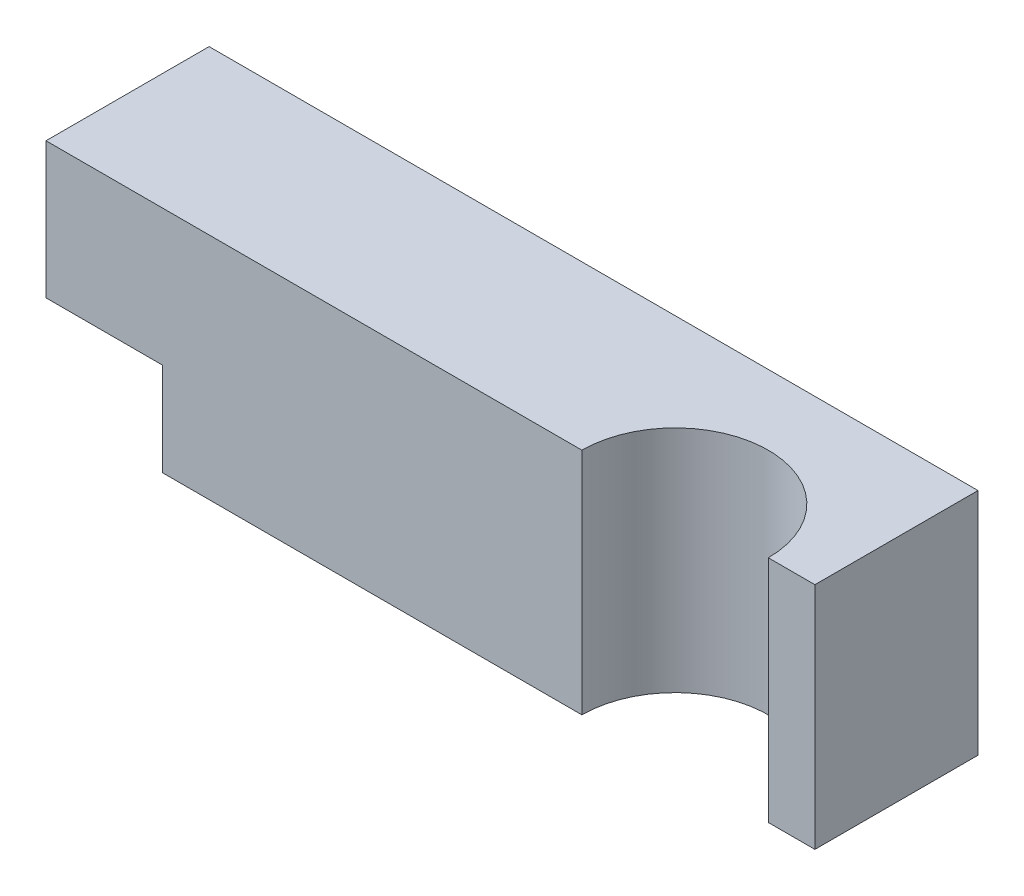
SolidWorks part; units mm, degrees
ref_plane "Front Plane" through (0, 0, 0) normal (0, 0, 1) x (1, 0, 0)
ref_plane "Top Plane" through (0, 0, 0) normal (0, 1, 0) x (1, 0, 0)
ref_plane "Right Plane" through (0, 0, 0) normal (1, 0, 0) x (0, 0, -1)
sketch "Sketch4" plane through (0, 0, 0) normal (0, 0, 1) x (1, 0, 0)
  line L1 (30.8815, 14.9647) -> (16.8815, 14.9647)
  line L2 (30.8815, 14.9647) -> (30.8815, 16.9647)
  line L4 (16.8815, 14.9647) -> (16.8815, 16.9647)
  line L5 (20.7026, 19.8847) -> (30.8815, 19.8847)
  line L6 (16.8815, 16.9647) -> (14.3815, 16.9647)
  line L8 (20.7026, 19.8847) -> (14.3815, 19.8847)
  line L9 (14.3815, 16.9647) -> (14.3815, 19.8847)
  line L10 (30.8815, 19.8847) -> (30.8815, 16.9647)
extrude "Boss-Extrude2" add sketch "Sketch4" along normal blind 3.5 separate body contours L6 L9 L8 L5 L10 L2 L1 L4
sketch "Sketch5" plane through (0, 19.8847, 0) normal (0, 1, 0) x (1, 0, 0)
  line L0 (30.8815, -3.5) -> (25.8815, -3.5)
  line L2 (30.8815, -3.5) -> (27.8815, -3.5)
  arc A0 (29.8815, -3.5) -> (25.8815, -3.5) centre (27.8815, -3.5) ccw
  line M3 (14.3815, -3.5) -> (30.8815, -3.5)
extrude "Cut-Extrude1" cut sketch "Sketch5" against normal blind 6 contours L0 A0 M3
